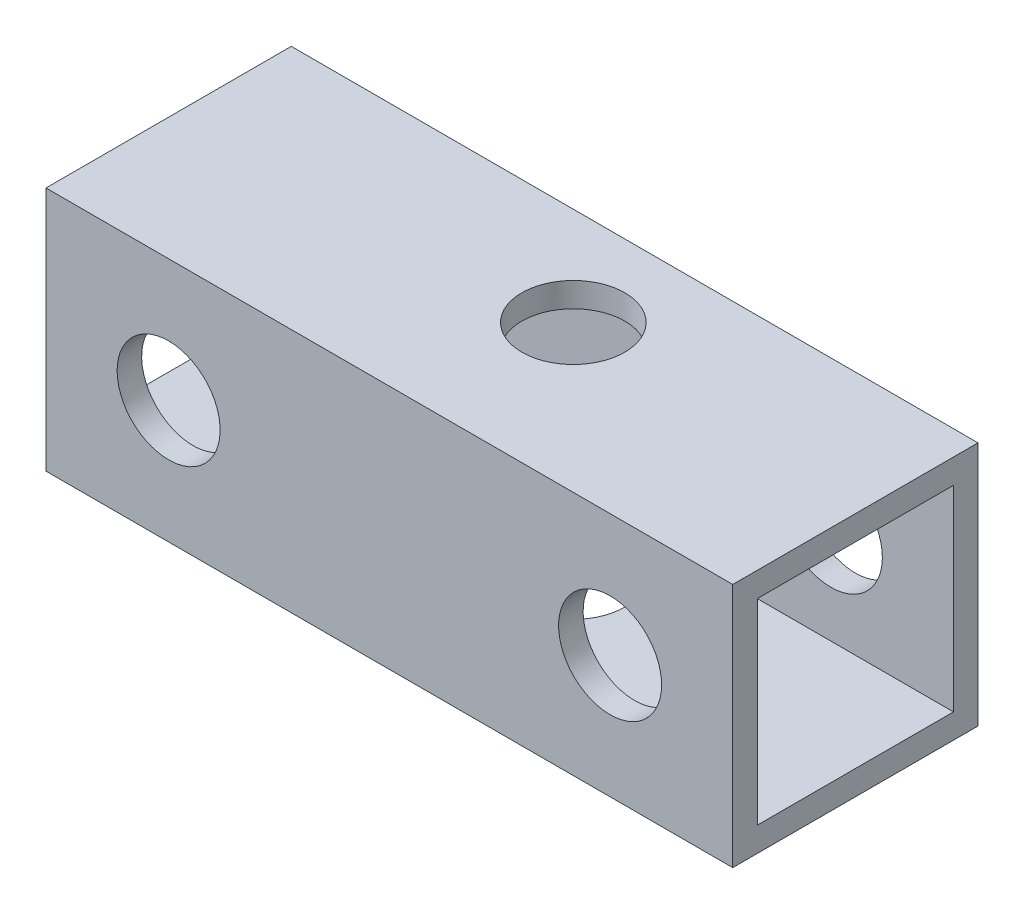
SolidWorks part; units mm, degrees
material "5052-H34"
ref_plane "正面" through (0, 0, 0) normal (0, 0, 1) x (1, 0, 0)
ref_plane "平面" through (0, 0, 0) normal (0, 1, 0) x (1, 0, 0)
ref_plane "右側面" through (0, 0, 0) normal (1, 0, 0) x (0, 0, -1)
sketch "ｽｹｯﾁ1" plane through (0, 0, 0) normal (1, 0, 0) x (0, 0, -1)
  line L1 (-5, 5) -> (5, 5)
  line L2 (-5, 5) -> (-5, -5)
  line L3 (-5, -5) -> (5, -5)
  line L4 (5, 5) -> (5, -5)
  line L5 (-5, 5) -> (5, -5) construction
  line L6 (-5, -5) -> (5, 5) construction
  point P0 (0, 0)
  dimension "D1" = 10
extrude "押し出し-薄板1" add sketch "ｽｹｯﾁ1" along normal blind 28 thin
sketch "ｽｹｯﾁ4" plane through (0, 0, 5) normal (0, 0, 1) x (1, 0, 0)
  line L0 (28, 0) -> (0, 0) construction
  line L1 (28, 5) -> (28, -5) construction
  line L2 (14, 0) -> (14, 5) construction
  line L3 (28, 5) -> (0, 5) construction
  circle A0 centre (23, 0) radius 2.1
  circle A1 centre (5, 0) radius 2.1
  dimension "D1" = 4.2
  dimension "D2" = 5
extrude "ｶｯﾄ - 押し出し3" cut sketch "ｽｹｯﾁ4" against normal through all
sketch "ｽｹｯﾁ5" plane through (0, 5, 0) normal (0, 1, 0) x (1, 0, 0)
  line L0 (28, 1) -> (15.5, 1) construction
  line L2 (28, 5) -> (0, 5) construction
  line L3 (28, 5) -> (28, -5) construction
  circle A0 centre (15.5, 1) radius 2.1
  dimension "D2" = 4.2
  dimension "D1" = 12.5
  dimension "D3" = 4
extrude "ｶｯﾄ - 押し出し4" cut sketch "ｽｹｯﾁ5" against normal through all
sketch "ｽｹｯﾁ6" plane through (0, 0, -5) normal (0, 0, -1) x (-1, 0, 0)
  circle A0 centre (-5, 0) radius 4
  dimension "D1" = 8
extrude "ｶｯﾄ - 押し出し5" cut sketch "ｽｹｯﾁ6" against normal blind 1
